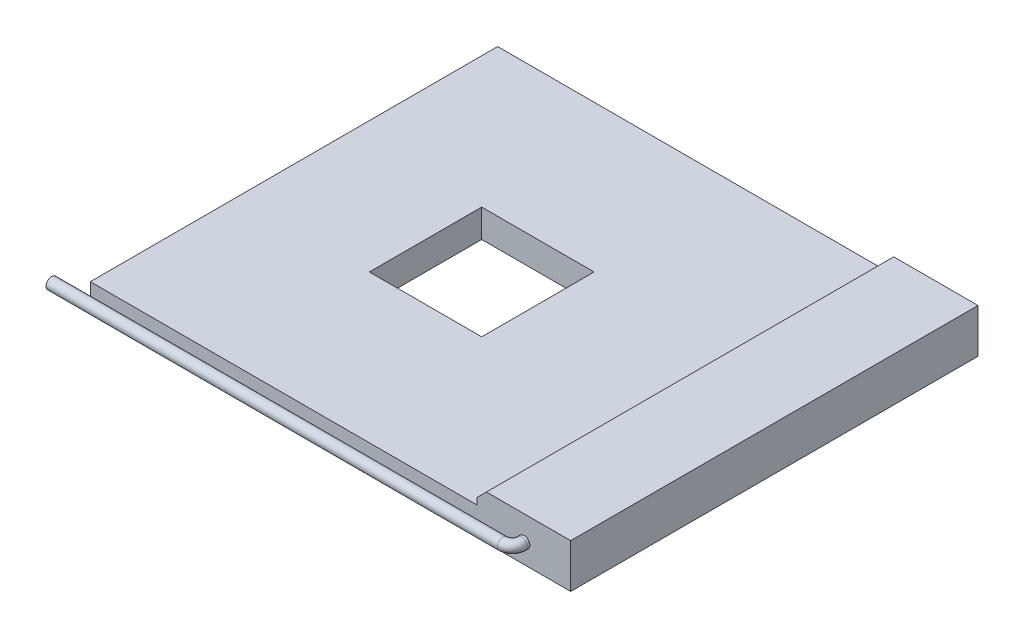
SolidWorks part; units mm, degrees
ref_plane "Front Plane" through (0, 0, 0) normal (0, 0, 1) x (1, 0, 0)
ref_plane "Top Plane" through (0, 0, 0) normal (0, 1, 0) x (1, 0, 0)
ref_plane "Right Plane" through (0, 0, 0) normal (1, 0, 0) x (0, 0, -1)
sketch "Sketch1" plane through (0, 0, 0) normal (0, 1, 0) x (1, 0, 0)
  line L1 (-25.65, -21.75) -> (25.65, -21.75)
  line L2 (-25.65, -21.75) -> (-25.65, 21.75)
  line L3 (-25.65, 21.75) -> (25.65, 21.75)
  line L4 (25.65, -21.75) -> (25.65, 21.75)
  line L5 (-25.65, -21.75) -> (25.65, 21.75) construction
  line L6 (-25.65, 21.75) -> (25.65, -21.75) construction
  point P0 (0, 0)
  dimension "D1" = 51.3
  dimension "D2" = 43.5
extrude "Boss-Extrude1" add sketch "Sketch1" along normal blind 3
sketch "Sketch2" plane through (0, 3, 0) normal (0, 1, 0) x (1, 0, 0)
  line L0 (25.65, 21.75) -> (-25.65, 21.75) construction
  line L1 (-11.65, 6.05) -> (0.35, 6.05)
  line L2 (-11.65, 6.05) -> (-11.65, -5.95)
  line L3 (-11.65, -5.95) -> (0.35, -5.95)
  line L4 (0.35, 6.05) -> (0.35, -5.95)
  line L5 (-25.65, 21.75) -> (-25.65, -21.75) construction
  dimension "D1" = 15.7
  dimension "D2" = 12
  dimension "D3" = 12
  dimension "D4" = 14
extrude "Cut-Extrude1" cut sketch "Sketch2" against normal blind 3
sketch "Sketch3" plane through (0, 3, 0) normal (0, 1, 0) x (1, 0, 0)
  line L0 (-25.65, -21.75) -> (25.65, -21.75) construction
  line L1 (25.65, 21.75) -> (15.65, 21.75)
  line L2 (25.65, 21.75) -> (25.65, -21.75)
  line L3 (25.65, -21.75) -> (15.65, -21.75)
  line L4 (15.65, 21.75) -> (15.65, -21.75)
  dimension "D1" = 10
extrude "Boss-Extrude2" add sketch "Sketch3" along normal blind 1.7
chamfer "Chamfer1" distance 1 angle 45 1 edges at (15.65, 4.7, 0)
sketch "Sketch4" plane through (0, 0, 21.75) normal (0, 0, 1) x (1, 0, 0)
  circle A0 centre (20.6865, 2.0949) radius 0.6
sketch "Sketch5" plane through (0, 3, 0) normal (0, 1, 0) x (1, 0, 0)
  line L0 (20.6865, -21.75) -> (20.6865, -22.0312)
  line L1 (20.0865, -21.75) -> (21.2865, -21.75) construction
  line L2 (19.6865, -23.0312) -> (-28.5027, -23.0312)
  arc A0 (20.6865, -22.0312) -> (19.6865, -23.0312) centre (19.6865, -22.0312) cw
  dimension "D1" = 1
sweep "handle" add profiles "Sketch4" path "Sketch5"
